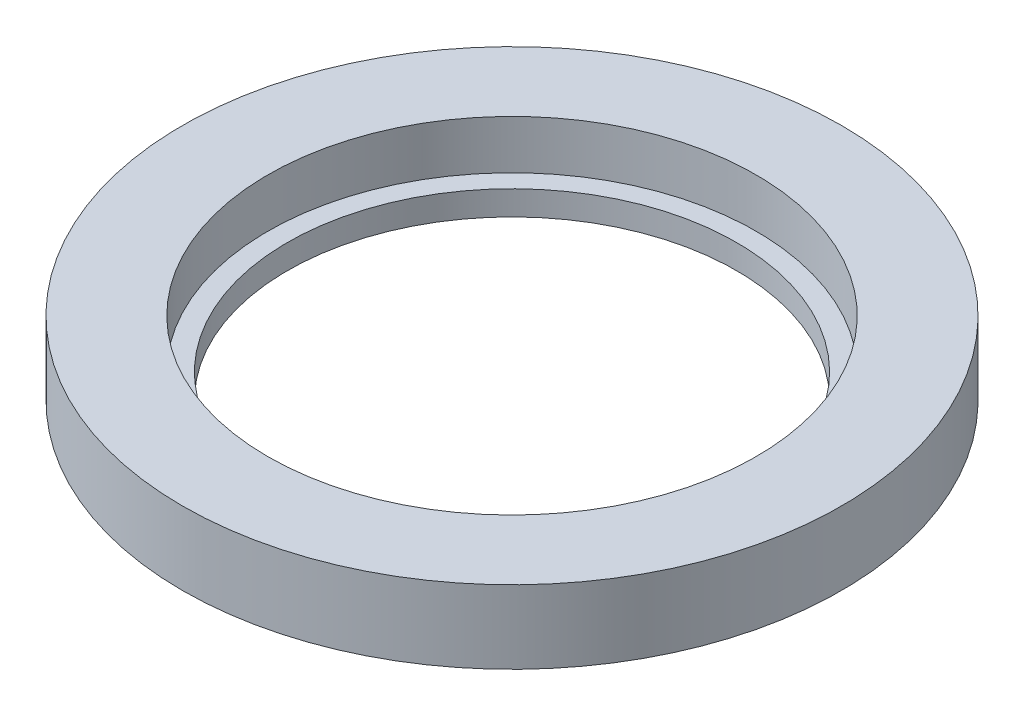
SolidWorks part; units mm, degrees
material "PA Type 6"
ref_plane "Front Plane" through (0, 0, 0) normal (0, 0, 1) x (1, 0, 0)
ref_plane "Top Plane" through (0, 0, 0) normal (0, 1, 0) x (1, 0, 0)
ref_plane "Right Plane" through (0, 0, 0) normal (1, 0, 0) x (0, 0, -1)
sketch "Sketch1" plane through (0, 0, 0) normal (0, 1, 0) x (1, 0, 0)
  circle A0 centre (0, 0) radius 33.75
  dimension "D1" = 67.5
extrude "Boss-Extrude1" add sketch "Sketch1" along normal blind 7.5
sketch "Sketch2" plane through (0, 0, 0) normal (0, -1, 0) x (1, 0, 0)
  line L0 (0, 33.75) -> (0, -33.75) construction
  line L1 (-33.75, 0) -> (33.75, 0) construction
  line L2 (0, 0) -> (-23.8649, -23.8649) construction
  circle A0 centre (0, 0) radius 33.75 construction
  circle A1 centre (-30, 0) radius 2.6
  circle A2 centre (30, 0) radius 2.6
  circle A3 centre (0, -30) radius 2.6
  circle A4 centre (0, 30) radius 2.6
  dimension "D2" = 5.2
  dimension "D3" = 30
  dimension "D1" = 45
extrude "Cut-Extrude1" cut sketch "Sketch2" against normal blind 2.5
sketch "Sketch3" plane through (0, 7.5, 0) normal (0, 1, 0) x (1, 0, 0)
  circle A0 centre (0, 0) radius 23
  dimension "D1" = 46
extrude "Cut-Extrude2" cut sketch "Sketch3" against normal through all
sketch "Sketch4" plane through (0, 7.5, 0) normal (0, 1, 0) x (1, 0, 0)
  circle A0 centre (0, 0) radius 25
  dimension "D1" = 50
extrude "Cut-Extrude3" cut sketch "Sketch4" against normal blind 5
